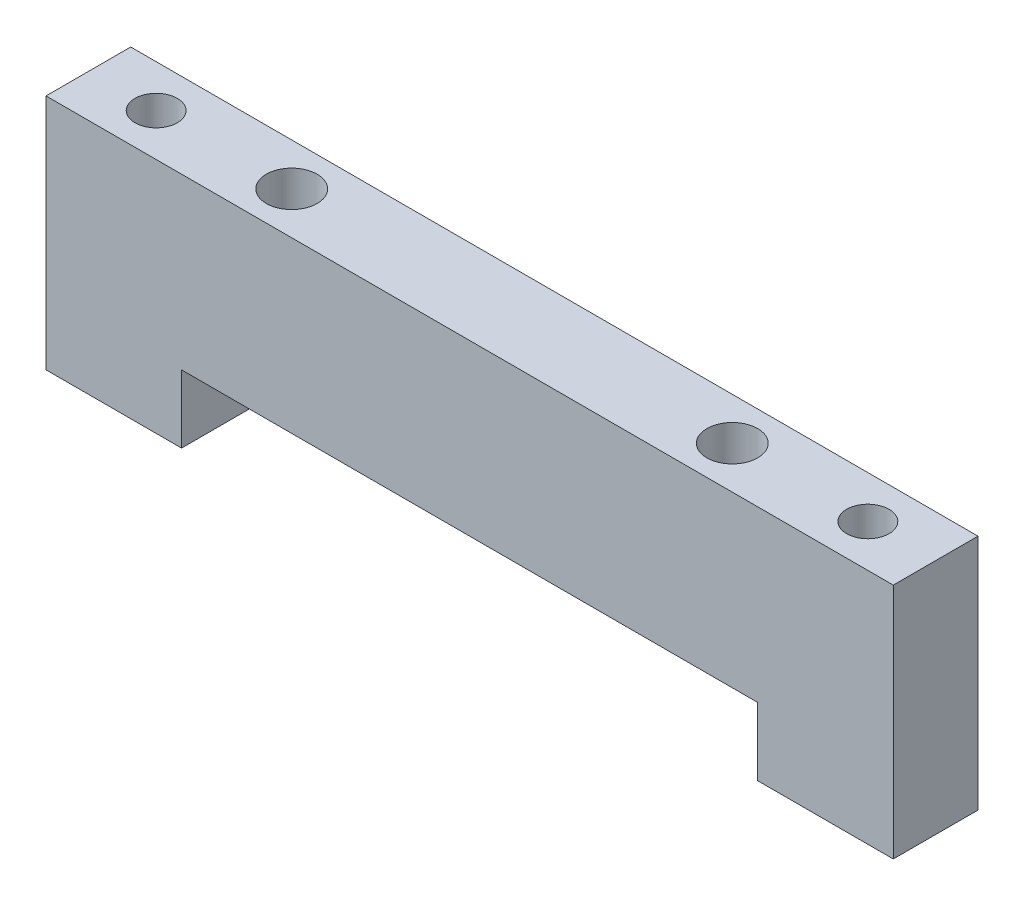
SolidWorks part; units mm, degrees
material "Alliage 1060"
ref_plane "Plan de face" through (0, 0, 0) normal (0, 0, 1) x (1, 0, 0)
ref_plane "Plan de dessus" through (0, 0, 0) normal (0, 1, 0) x (1, 0, 0)
ref_plane "Plan de droite" through (0, 0, 0) normal (1, 0, 0) x (0, 0, -1)
sketch "Esquisse1" plane through (0, 0, 0) normal (0, 0, 1) x (1, 0, 0)
  line L0 (-25, 0) -> (-17, 0)
  line L1 (-17, 0) -> (-17, 4)
  line L2 (-17, 4) -> (17, 4)
  line L3 (17, 4) -> (17, 0)
  line L4 (17, 0) -> (25, 0)
  line L5 (25, 0) -> (25, 14)
  line L6 (25, 14) -> (-25, 14)
  line L7 (-25, 14) -> (-25, 0)
  line L8 (0, 0) -> (0, 54.577) construction
  dimension "D1" = 50
  dimension "D2" = 34
  dimension "D3" = 4
  dimension "D4" = 14
extrude "Extrusion1" add sketch "Esquisse1" along normal blind 5
sketch "Esquisse3" plane through (0, 14, 0) normal (0, 1, 0) x (1, 0, 0)
  circle A0 centre (13, -2.5) radius 1.5 construction
  circle A1 centre (-13, -2.5) radius 1.5 construction
  circle A2 centre (13, -2.5) radius 1.5
  circle A3 centre (-13, -2.5) radius 1.5
extrude "Enlèv. mat.-Extru.1" cut sketch "Esquisse3" against normal through all
hole_wizard "Trou taraudé M3x0.51" positions "Esquisse5" profile "Esquisse6" tap size "M3x0.5" standard "Ansi Métrique" end condition through all
sketch "Esquisse5" plane through (0, 0, 0) normal (0, -1, 0) x (1, 0, 0)
  line L0 (-21, 2.5) -> (21, 2.5) construction
  line L3 (-25, 0) -> (-17, 0) construction
  line L4 (-25, 5) -> (-17, 5) construction
  line L5 (0, 0) -> (0, 2.5) construction
  point P0 (-21, 2.5)
  point P1 (21, 2.5)
  dimension "D1" = 42
sketch "Esquisse6" plane through (-21, 0, 2.5) normal (1, 0, 0) x (0, 0, -1)
  line L0 (0, 0) -> (0, 14)
  line L1 (0, 14) -> (1.25, 14)
  line L2 (1.25, 14) -> (1.25, 0)
  line L5 (1.25, 0) -> (0, 0)
  line L11 (0, -6.35) -> (0, 107.95) construction
  dimension "Diamètre du trou pour taraudage jusqu'au prochain" = 2.5
  dimension "Profondeur du trou pour taraudage jusqu'au prochain" = 14
cosmetic thread "Filetage de perçage1" parameters "D2"=3
cosmetic thread "Filetage de perçage2" parameters "D2"=3
